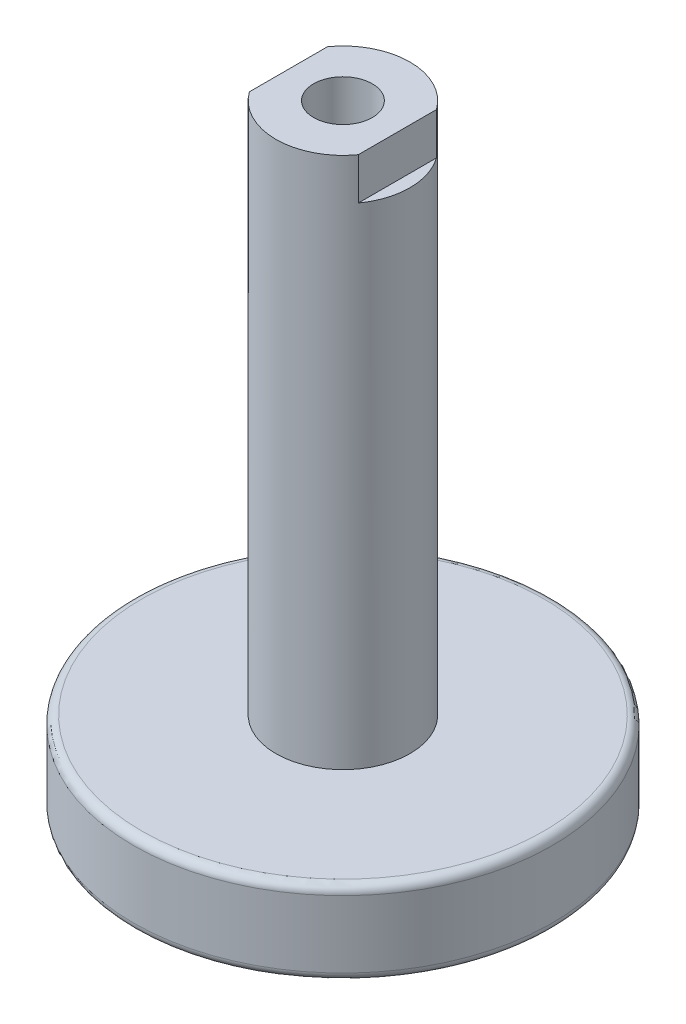
SolidWorks part; units mm, degrees
material "201 Annealed Stainless Steel (SS)"
ref_plane "Front Plane" through (0, 0, 0) normal (0, 0, 1) x (1, 0, 0)
ref_plane "Top Plane" through (0, 0, 0) normal (0, 1, 0) x (1, 0, 0)
ref_plane "Right Plane" through (0, 0, 0) normal (1, 0, 0) x (0, 0, -1)
sketch "Sketch1" plane through (0, 0, 0) normal (0, 1, 0) x (1, 0, 0)
  circle A0 centre (0, 0) radius 25
  dimension "D1" = 50
extrude "Boss-Extrude1" add sketch "Sketch1" along normal blind 10
fillet "Fillet1" radius 1 2 edges at (0, 0, 25) (0, 10, 25)
sketch "Sketch2" plane through (0, 10, 0) normal (0, 1, 0) x (1, 0, 0)
  circle A0 centre (0, 0) radius 8
  dimension "D1" = 16
extrude "Boss-Extrude2" add sketch "Sketch2" along normal blind 63.5
hole_wizard "M8x1.0 Tapped Hole1" positions "Sketch4" profile "Sketch3" tap size "M8x1.0" standard "ANSI Metric"
sketch "Sketch4" plane through (0, 73.5, 0) normal (0, 1, 0) x (1, 0, 0)
  point P0 (0, 0)
sketch "Sketch3" plane through (0, 73.5, 0) normal (1, 0, 0) x (0, 0, 1)
  line L0 (0, 0) -> (0, 14.103)
  line L1 (0, 14.103) -> (3.5, 12)
  line L2 (3.5, 12) -> (3.5, 0)
  line L5 (3.5, 0) -> (0, 0)
  line L10 (0, 14.103) -> (-3.5, 12) construction
  line L11 (0, -6.35) -> (0, 107.95) construction
  dimension "Tap Drill Dia." = 7
  dimension "Tap Drill Depth" = 12
  dimension "Drill Angle" = 118
sketch "Sketch5" plane through (0, 73.5, 0) normal (0, 1, 0) x (1, 0, 0)
  line L1 (-6.5, 9.0724) -> (6.5, 9.0724)
  line L2 (-6.5, 9.0724) -> (-6.5, -9.0724)
  line L3 (-6.5, -9.0724) -> (6.5, -9.0724)
  line L4 (6.5, 9.0724) -> (6.5, -9.0724)
  line L5 (-6.5, 9.0724) -> (6.5, -9.0724) construction
  line L6 (-6.5, -9.0724) -> (6.5, 9.0724) construction
  point P0 (0, 0)
  dimension "D1" = 13
extrude "Cut-Extrude1" cut sketch "Sketch5" against normal blind 5 flip side to cut
